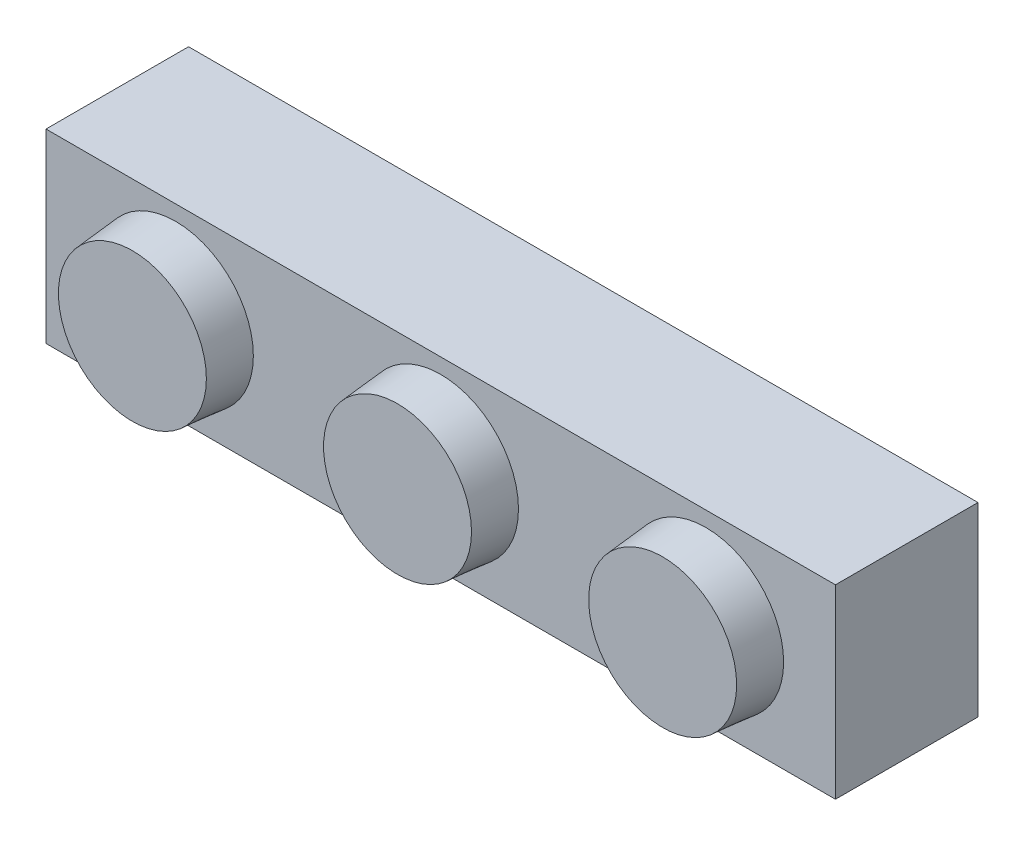
SolidWorks part; units mm, degrees
ref_plane "Front" through (0, 0, 0) normal (0, 0, 1) x (1, 0, 0)
ref_plane "Top" through (0, 0, 0) normal (0, 1, 0) x (1, 0, 0)
ref_plane "Right" through (0, 0, 0) normal (1, 0, 0) x (0, 0, -1)
sketch "Sketch1" plane through (0, 0, 0) normal (0, 1, 0) x (1, 0, 0)
  line L1 (-1160.4625, 209.55) -> (1160.4625, 209.55)
  line L2 (-1160.4625, 209.55) -> (-1160.4625, -209.55)
  line L3 (-1160.4625, -209.55) -> (1160.4625, -209.55)
  line L4 (1160.4625, 209.55) -> (1160.4625, -209.55)
  line L5 (-1160.4625, 209.55) -> (1160.4625, -209.55) construction
  line L6 (-1160.4625, -209.55) -> (1160.4625, 209.55) construction
  point P0 (0, 0)
  dimension "D1" = 2320.925
  dimension "D2" = 419.1
extrude "Boss-Extrude1" add sketch "Sketch1" along normal blind 546.1
sketch "Sketch2" plane through (0, 0, 209.55) normal (0, 0, 1) x (1, 0, 0)
  line L0 (0, 0) -> (0, 546.1) construction
  line L1 (-1160.4625, 546.1) -> (1160.4625, 546.1) construction
  line L2 (0, 273.05) -> (-1160.4625, 273.05) construction
  line L3 (-1160.4625, 546.1) -> (-1160.4625, 0) construction
  line L4 (0, 273.05) -> (1160.4625, 273.05) construction
  line L5 (1160.4625, 546.1) -> (1160.4625, 0) construction
  circle A0 centre (0, 273.05) radius 228.6
  circle A1 centre (779.4625, 273.05) radius 228.6
  circle A2 centre (-779.4625, 273.05) radius 228.6
  dimension "D1" = 457.2
  dimension "D3" = 381
  dimension "D2" = 381
extrude "Boss-Extrude2" add sketch "Sketch2" along normal blind 127 draft 5
